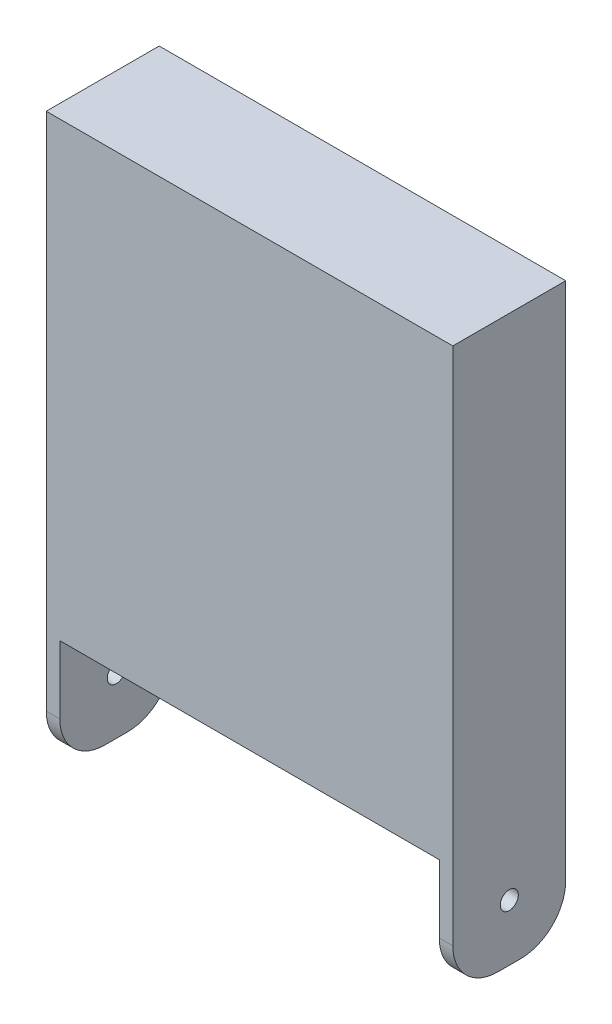
SolidWorks part; units mm, degrees
ref_plane "前视基准面" through (0, 0, 0) normal (0, 0, 1) x (1, 0, 0)
ref_plane "上视基准面" through (0, 0, 0) normal (0, 1, 0) x (1, 0, 0)
ref_plane "右视基准面" through (0, 0, 0) normal (1, 0, 0) x (0, 0, -1)
sketch "Sketch1" plane through (0, 0, 0) normal (0, 1, 0) x (1, 0, 0)
  line L1 (-90, 25) -> (90, 25)
  line L2 (-90, 25) -> (-90, -25)
  line L3 (-90, -25) -> (90, -25)
  line L4 (90, 25) -> (90, -25)
  line L5 (-90, 25) -> (90, -25) construction
  line L6 (-90, -25) -> (90, 25) construction
  point P0 (0, 0)
extrude "Extrude1" add sketch "Sketch1" along normal blind 200
sketch "Sketch2" plane through (0, 0, 0) normal (0, -1, 0) x (1, 0, 0)
  line L0 (90, -25) -> (-90, -25) construction
  line L1 (-90, 25) -> (-84, 25)
  line L2 (-90, 25) -> (-90, -25)
  line L3 (-90, -25) -> (-84, -25)
  line L4 (-84, 25) -> (-84, -25)
  line L6 (90, 25) -> (84, 25)
  line L7 (90, 25) -> (90, -25)
  line L8 (90, -25) -> (84, -25)
  line L9 (84, 25) -> (84, -25)
extrude "Extrude2" add sketch "Sketch2" along normal blind 50
sketch "Sketch3" plane through (84, 0, 0) normal (-1, 0, 0) x (0, 0, 1)
  circle A0 centre (0, -25) radius 4
extrude "Extrude3" cut sketch "Sketch3" against normal blind 40 and the other way blind 477
fillet "Fillet1" radius 20 4 edges at (-87, -50, -25) (-87, -50, 25) (87, -50, -25) (87, -50, 25)
